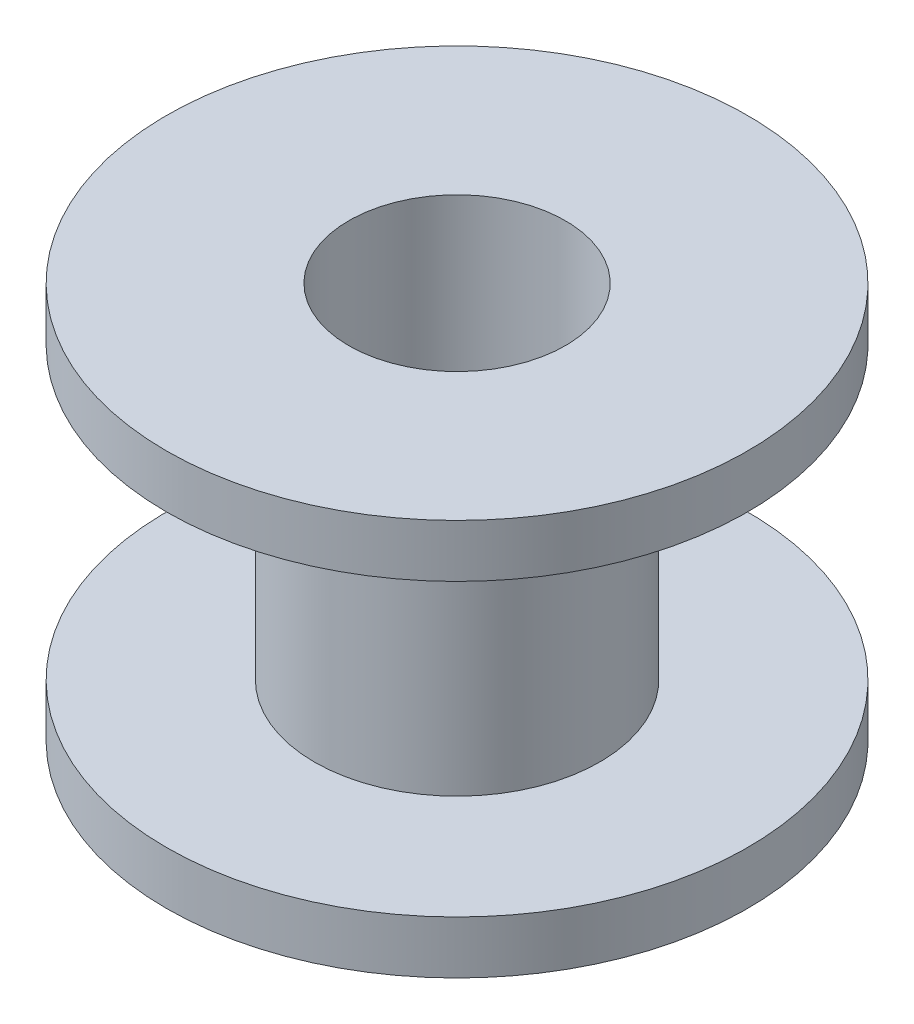
SolidWorks part; units mm, degrees
material "ABS"
ref_plane "Front Plane" through (0, 0, 0) normal (0, 0, 1) x (1, 0, 0)
ref_plane "Top Plane" through (0, 0, 0) normal (0, 1, 0) x (1, 0, 0)
ref_plane "Right Plane" through (0, 0, 0) normal (1, 0, 0) x (0, 0, -1)
sketch "Sketch1" plane through (0, 0, 0) normal (1, 0, 0) x (0, 0, -1)
  line L0 (0, 44.6591) -> (0, -36.1364) construction
  line L1 (-5.4, 5.5) -> (-5.4, -5.5)
  line L2 (-5.4, -5.5) -> (-11, -5.5)
  line L3 (-11, -5.5) -> (-11, -7.5)
  line L4 (-11, -7.5) -> (-4.1, -7.5)
  line L5 (-4.1, -7.5) -> (-4.1, 7.5)
  line L9 (-33.5795, 0) -> (17.0455, 0) construction
  line L10 (-11, 5.5) -> (-11, 7.5)
  line L11 (-11, 7.5) -> (-4.1, 7.5)
  line L12 (-5.4, 5.5) -> (-11, 5.5)
  point P3 (-5.4, 0)
  point P15 (-4.1, 0)
  dimension "D1" = 7.5
  dimension "D2" = 22
  dimension "D3" = 8.2
  dimension "D4" = 2
  dimension "D5" = 10.8
revolve "Revolve1" add sketch "Sketch1" angle 360 about L0
